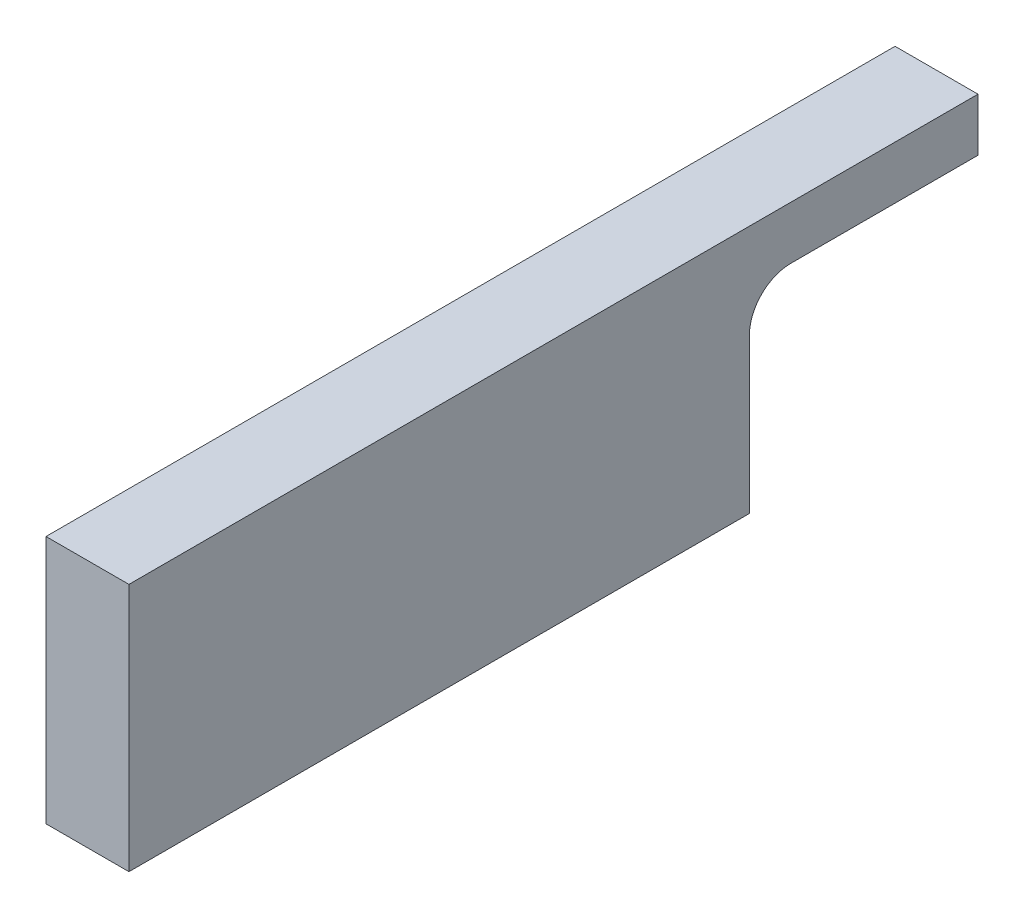
SolidWorks part; units mm, degrees
material "Low Carbon Steel"
ref_plane "Front Plane" through (0, 0, 0) normal (0, 0, 1) x (1, 0, 0)
ref_plane "Top Plane" through (0, 0, 0) normal (0, 1, 0) x (1, 0, 0)
ref_plane "Right Plane" through (0, 0, 0) normal (1, 0, 0) x (0, 0, -1)
sketch "Sketch2" plane through (0, 0, 0) normal (1, 0, 0) x (0, 0, -1)
  line L0 (-130, -38.1) -> (130, 38.1) construction
  line L1 (-130, 38.1) -> (130, 38.1)
  line L2 (-130, 38.1) -> (-130, -38.1)
  line L3 (-130, -38.1) -> (60, -38.1)
  line L4 (130, 38.1) -> (130, 21.9)
  line L5 (130, 21.9) -> (72.7, 21.9)
  line L6 (60, 9.2) -> (60, -38.1)
  arc A0 (72.7, 21.9) -> (60, 9.2) centre (72.7, 9.2) ccw
  point P9 (60, 21.9)
  dimension "D5" = 12.7
  dimension "D1" = 260
  dimension "D2" = 76.2
  dimension "D3" = 60
  dimension "D4" = 70
extrude "Boss-Extrude1" add sketch "Sketch2" along normal mid plane 25.4
other "Freeze***"
